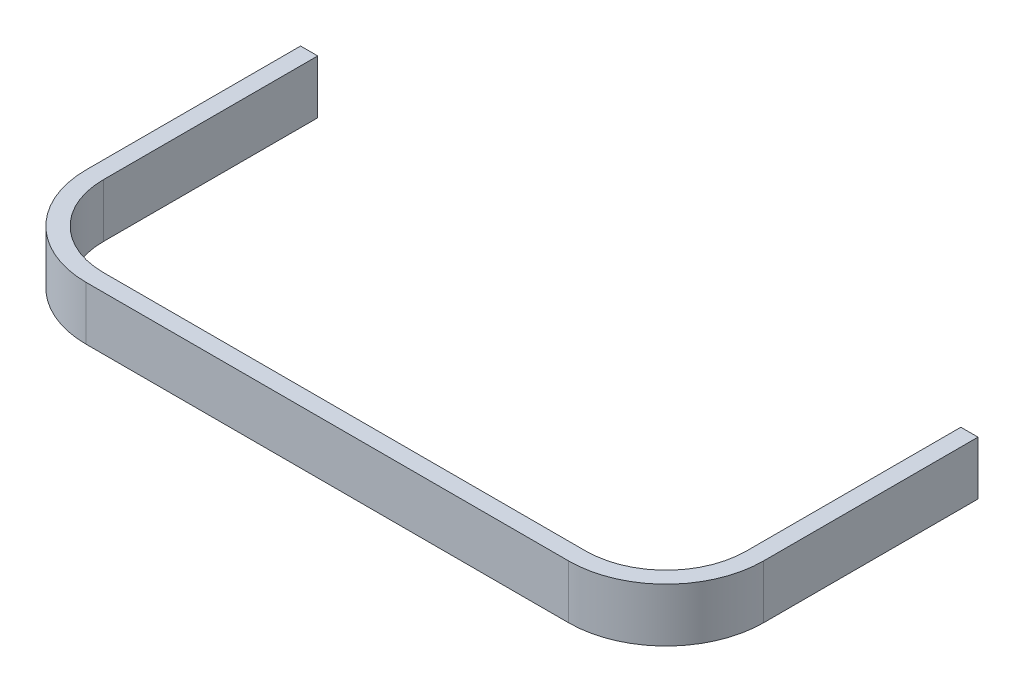
SolidWorks part; units mm, degrees
ref_plane "Front Plane" through (0, 0, 0) normal (0, 0, 1) x (1, 0, 0)
ref_plane "Top Plane" through (0, 0, 0) normal (0, 1, 0) x (1, 0, 0)
ref_plane "Right Plane" through (0, 0, 0) normal (1, 0, 0) x (0, 0, -1)
sketch "Sketch474" plane through (0, 0, 0) normal (0, 1, 0) x (1, 0, 0)
  line L4 (-76.2, 0) -> (-76.2, -50.8)
  line L5 (-57.15, -69.85) -> (57.15, -69.85)
  line L7 (76.2, 0) -> (76.2, -50.8)
  line L8 (-80.264, 0) -> (-80.264, -50.8)
  line L9 (-57.15, -73.914) -> (57.15, -73.914)
  line L10 (80.264, 0) -> (80.264, -50.8)
  line L11 (-76.2, 0) -> (-80.264, 0)
  line L12 (76.2, 0) -> (80.264, 0)
  line L13 (-76.2, 0) -> (76.2, 0) construction
  arc A2 (-76.2, -50.8) -> (-57.15, -69.85) centre (-57.15, -50.8) ccw
  arc A3 (57.15, -69.85) -> (76.2, -50.8) centre (57.15, -50.8) ccw
  arc A4 (-80.264, -50.8) -> (-57.15, -73.914) centre (-57.15, -50.8) ccw
  arc A5 (57.15, -73.914) -> (80.264, -50.8) centre (57.15, -50.8) ccw
  dimension "D4" = 19.05
  dimension "D1" = 4.064
  dimension "D2" = 69.85
  dimension "D3" = 152.4
extrude "Boss-Extrude4" add sketch "Sketch474" along normal blind 12.7
